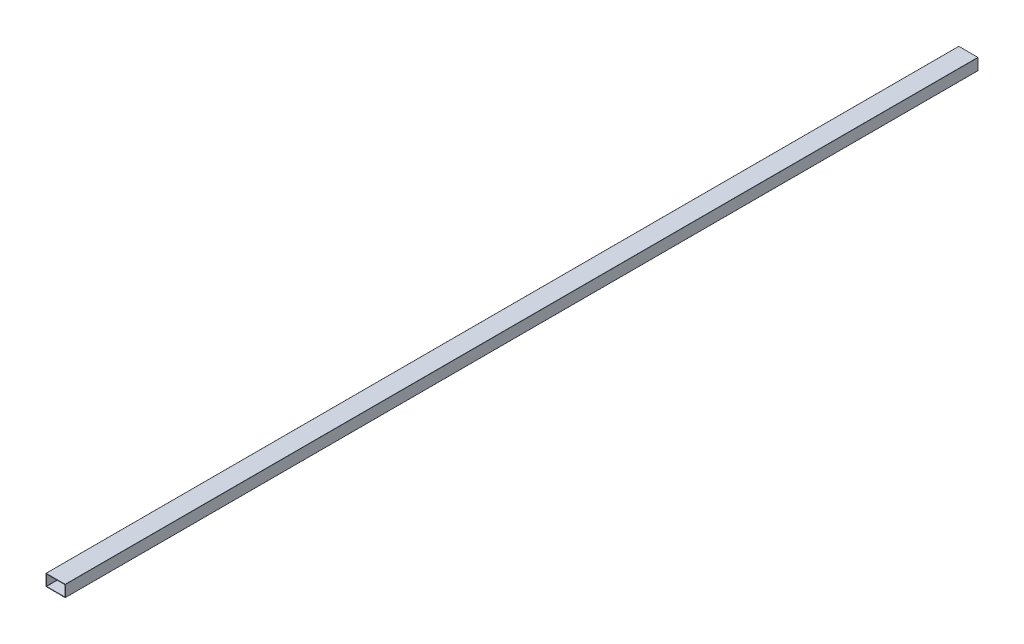
SolidWorks part; units mm, degrees
material "AISI 1035 Acero (SS)"
ref_plane "Alzado" through (0, 0, 0) normal (0, 0, 1) x (1, 0, 0)
ref_plane "Planta" through (0, 0, 0) normal (0, 1, 0) x (1, 0, 0)
ref_plane "Vista lateral" through (0, 0, 0) normal (1, 0, 0) x (0, 0, -1)
sketch "Croquis1" plane through (0, 0, 0) normal (0, 0, 1) x (1, 0, 0)
  line L0 (-60.46, -35.06) -> (-60.46, 35.06)
  line L1 (-63.5, -38.1) -> (63.5, -38.1)
  line L2 (-63.5, -38.1) -> (-63.5, 38.1)
  line L3 (-63.5, 38.1) -> (63.5, 38.1)
  line L4 (63.5, -38.1) -> (63.5, 38.1)
  line L5 (-63.5, -38.1) -> (63.5, 38.1) construction
  line L6 (-63.5, 38.1) -> (63.5, -38.1) construction
  line L7 (-60.46, 35.06) -> (60.46, 35.06)
  line L8 (60.46, -35.06) -> (60.46, 35.06)
  line L9 (-60.46, -35.06) -> (60.46, -35.06)
  point P0 (0, 0)
  dimension "D1" = 76.2
  dimension "D2" = 127
  dimension "D3" = 3.04
extrude "Saliente-Extruir1" add sketch "Croquis1" against normal blind 6000
fillet "Redondeo1" radius 1 8 edges at (-60.46, 35.06, -3000) (60.46, 35.06, -3000) (60.46, -35.06, -3000) (-63.5, -38.1, -3000) (-63.5, 38.1, -3000) (-60.46, -35.06, -3000) (63.5, -38.1, -3000) (63.5, 38.1, -3000)
